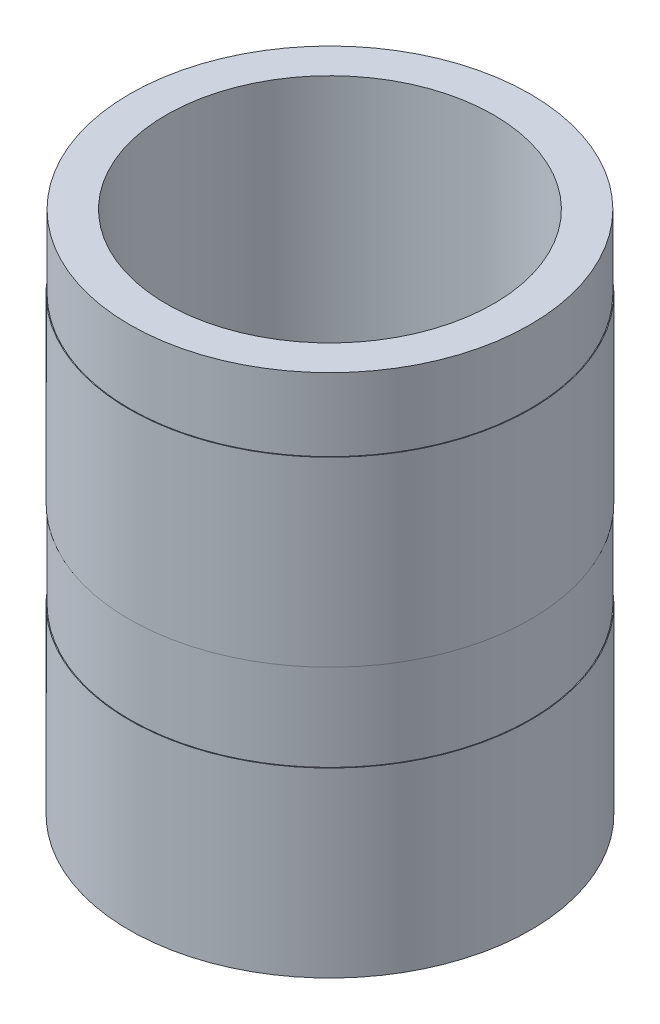
SolidWorks part; units mm, degrees
material "Polyurethane Foam Flexible"
ref_plane "Front" through (0, 0, 0) normal (0, 0, 1) x (1, 0, 0)
ref_plane "Top" through (0, 0, 0) normal (0, 1, 0) x (1, 0, 0)
ref_plane "Right" through (0, 0, 0) normal (1, 0, 0) x (0, 0, -1)
sketch "Sketch1" plane through (0, 0, 0) normal (0, 0, 1) x (1, 0, 0)
  line L0 (0, 0) -> (0, 63.9032) construction
  line L1 (27.6, 62) -> (27.5, 62)
  line L2 (22.5, 0) -> (27.5, 0)
  line L3 (22.5, 0) -> (22.5, 72)
  line L4 (22.5, 72) -> (27.5, 72)
  line L5 (27.5, 0) -> (27.5, 72)
  line L6 (27.6, 62) -> (27.6, 37)
  line L7 (27.6, 37) -> (27.5, 37)
  line L8 (27.5, 25) -> (27.6, 25)
  line L9 (27.6, 25) -> (27.6, 0)
  line L10 (27.6, 0) -> (27.5, 0)
  dimension "D1" = 22.5
  dimension "D2" = 72
  dimension "D3" = 5
  dimension "D4" = 0.1
  dimension "D5" = 25
  dimension "D6" = 10
  dimension "D7" = 25
  dimension "D8" = 12
revolve "Revolve1" add sketch "Sketch1" angle 360 about L0
